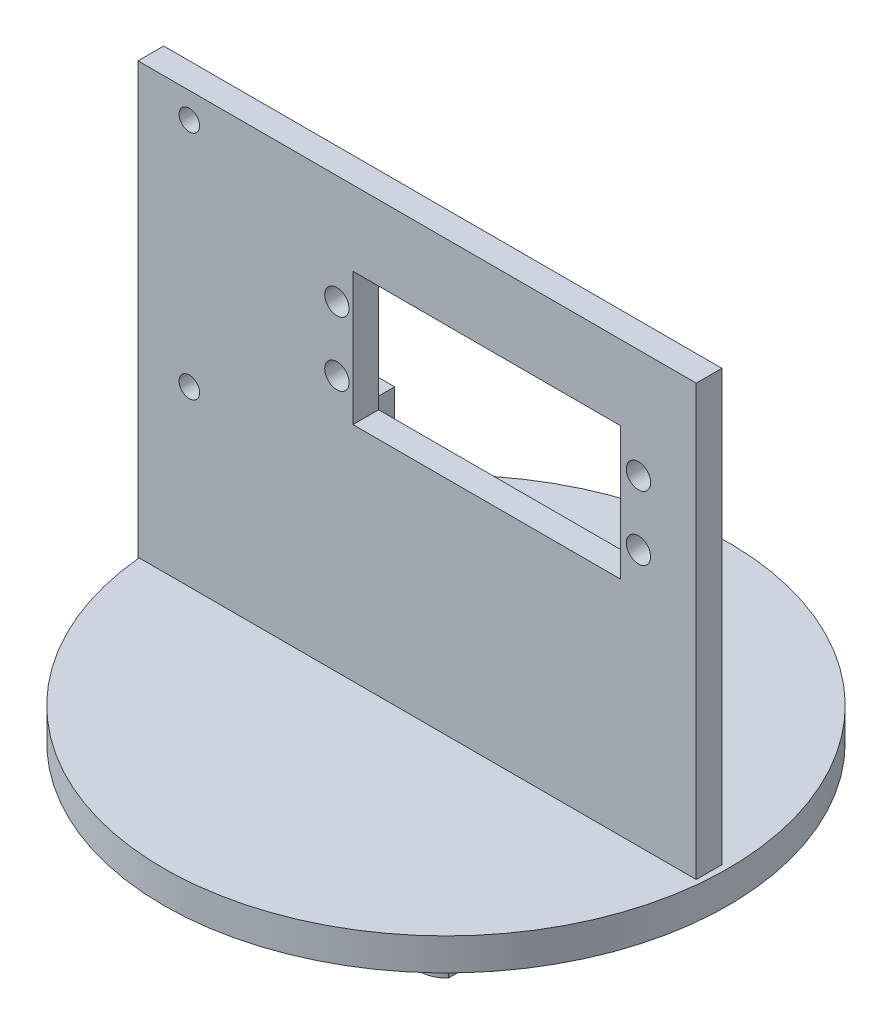
SolidWorks part; units mm, degrees
ref_plane "Front Plane" through (0, 0, 0) normal (0, 0, 1) x (1, 0, 0)
ref_plane "Top Plane" through (0, 0, 0) normal (0, 1, 0) x (1, 0, 0)
ref_plane "Right Plane" through (0, 0, 0) normal (1, 0, 0) x (0, 0, -1)
sketch "Yaw_platform_profile" plane through (0, 0, 0) normal (0, 1, 0) x (1, 0, 0)
  circle A0 centre (0, 0) radius 44
  dimension "D1" = 88
extrude "Yaw_platform" add sketch "Yaw_platform_profile" along normal blind 5 from offset 72
sketch "Printed_hollow_yaw_spindle_profile" plane through (0, 0, 0) normal (0, 1, 0) x (1, 0, 0)
  circle A0 centre (0, 0) radius 3.95
  circle A1 centre (0, 0) radius 1.75
  dimension "D1" = 7.9
  dimension "D2" = 3.5
extrude "Printed_hollow_yaw_spindle" add sketch "Printed_hollow_yaw_spindle_profile" along normal blind 29 from offset 43
sketch "Inner_race_load_shoulder_profile" plane through (0, 0, 0) normal (0, 1, 0) x (1, 0, 0)
  circle A0 centre (0, 0) radius 6
  circle A1 centre (0, 0) radius 1.75
  dimension "D1" = 12
  dimension "D2" = 3.5
extrude "Inner_race_load_shoulder" add sketch "Inner_race_load_shoulder_profile" along normal blind 2 from offset 70
sketch "D_flat_drive_key_profile" plane through (0, 0, 0) normal (0, 1, 0) x (1, 0, 0)
  line L1 (3, -5) -> (6, -5)
  line L2 (3, -5) -> (3, 5)
  line L3 (3, 5) -> (6, 5)
  line L4 (6, -5) -> (6, 5)
  dimension "D1" = 3
  dimension "D2" = 10
extrude "D_flat_on_spindle_end" cut sketch "D_flat_drive_key_profile" along normal blind 5 from offset 43
sketch "Shoulder_mount_plate_profile" plane through (0, 0, 0) normal (0, 0, 1) x (1, 0, 0)
  line L1 (-44, 76) -> (43, 76)
  line L2 (-44, 76) -> (-44, 144)
  line L3 (-44, 144) -> (43, 144)
  line L4 (43, 76) -> (43, 144)
  dimension "D1" = 87
  dimension "D2" = 68
extrude "Shoulder_mount_plate" add sketch "Shoulder_mount_plate_profile" along normal blind 4
sketch "MG996_body_window_profile" plane through (0, 0, 0) normal (0, 0, 1) x (1, 0, 0)
  line L1 (-10.5, 111.65) -> (31.2, 111.65)
  line L2 (-10.5, 111.65) -> (-10.5, 132.35)
  line L3 (-10.5, 132.35) -> (31.2, 132.35)
  line L4 (31.2, 111.65) -> (31.2, 132.35)
  dimension "D1" = 41.7
  dimension "D2" = 20.7
extrude "MG996_body_window" cut sketch "MG996_body_window_profile" along normal through all from offset 5
sketch "MG996_tab_mounts_profile" plane through (0, 0, 0) normal (0, 0, 1) x (1, 0, 0)
  circle A0 centre (-13, 117) radius 1.9
  circle A1 centre (-13, 127) radius 1.9
  circle A2 centre (34, 117) radius 1.9
  circle A3 centre (34, 127) radius 1.9
  dimension "D1" = 3.8
  dimension "D2" = 3.8
  dimension "D3" = 3.8
  dimension "D4" = 3.8
extrude "MG996_tab_mounts" cut sketch "MG996_tab_mounts_profile" along normal through all from offset 50
sketch "Passive_shoulder_standoffs_profile" plane through (0, 0, 0) normal (0, 0, 1) x (1, 0, 0)
  circle A0 centre (-36, 104) radius 1.6
  circle A1 centre (-36, 140) radius 1.6
  dimension "D1" = 3.2
  dimension "D2" = 3.2
extrude "Passive_shoulder_standoffs" cut sketch "Passive_shoulder_standoffs_profile" along normal through all from offset 50
sketch "Upright_rib_profile" plane through (0, 0, 0) normal (0, 0, 1) x (1, 0, 0)
  line L1 (-23, 77) -> (-16, 77)
  line L2 (-23, 77) -> (-23, 108)
  line L3 (-23, 108) -> (-16, 108)
  line L4 (-16, 77) -> (-16, 108)
  dimension "D1" = 7
  dimension "D2" = 31
extrude "Upright_rib" add sketch "Upright_rib_profile" along normal blind 12 from offset 8
sketch "Yaw_positive_retention_crossbolt_profile" plane through (0, 0, 0) normal (1, 0, 0) x (0, 0, -1)
  circle A0 centre (0, 45.5) radius 1.1
  dimension "D1" = 2.2
extrude "Yaw_positive_retention_crossbolt" cut sketch "Yaw_positive_retention_crossbolt_profile" along normal through all from offset 10
